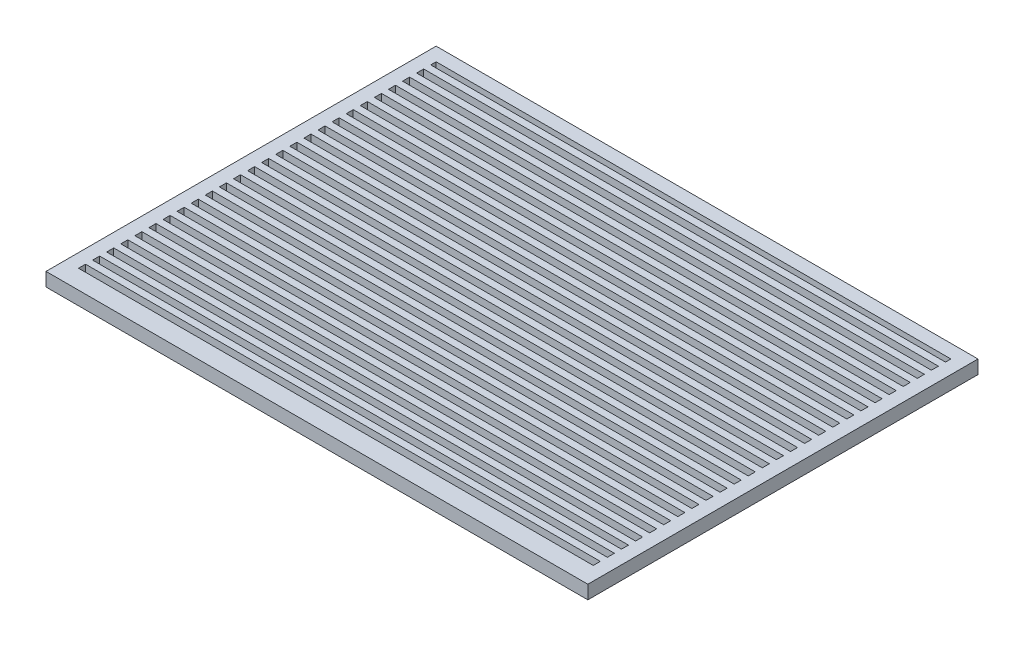
SolidWorks part; units mm, degrees
ref_plane "Front Plane" through (0, 0, 0) normal (0, 0, 1) x (1, 0, 0)
ref_plane "Top Plane" through (0, 0, 0) normal (0, 1, 0) x (1, 0, 0)
ref_plane "Right Plane" through (0, 0, 0) normal (1, 0, 0) x (0, 0, -1)
sketch "Sketch1" plane through (0, 0, 0) normal (0, 1, 0) x (1, 0, 0)
  line L1 (0, 0) -> (200, 0)
  line L2 (0, 0) -> (0, 144)
  line L3 (0, 144) -> (200, 144)
  line L4 (200, 0) -> (200, 144)
  dimension "D1" = 200
  dimension "D2" = 144
extrude "Boss-Extrude1" add sketch "Sketch1" along normal blind 5
sketch "Sketch2" plane through (0, 5, 0) normal (0, 1, 0) x (1, 0, 0)
  line L0 (0, 144) -> (0, 0) construction
  line L1 (5, 139) -> (195, 139)
  line L2 (5, 139) -> (5, 5)
  line L3 (5, 5) -> (195, 5)
  line L4 (195, 139) -> (195, 5)
  line L5 (200, 0) -> (200, 144) construction
  line L6 (200, 144) -> (0, 144) construction
  line L7 (0, 0) -> (200, 0) construction
  line L8 (5, 7) -> (195, 7)
  line L9 (195, 18.4551) -> (195, 31.4844)
  line L10 (5, 9.6) -> (195, 9.6)
  line L11 (5, 31.4844) -> (5, 45.5994)
  line L12 (5, 12.2) -> (195, 12.2)
  line L13 (195, 45.5994) -> (195, 72)
  line L14 (5, 14.8) -> (195, 14.8)
  line L15 (5, 72) -> (5, 70.9341)
  line L16 (5, 17.4) -> (195, 17.4)
  line L17 (5, 20) -> (195, 20)
  line L18 (5, 22.6) -> (195, 22.6)
  line L19 (5, 25.2) -> (195, 25.2)
  line L20 (5, 27.8) -> (195, 27.8)
  line L21 (5, 30.4) -> (195, 30.4)
  line L22 (5, 33) -> (195, 33)
  line L23 (5, 35.6) -> (195, 35.6)
  line L24 (5, 38.2) -> (195, 38.2)
  line L25 (5, 40.8) -> (195, 40.8)
  line L26 (5, 43.4) -> (195, 43.4)
  line L27 (5, 46) -> (195, 46)
  line L28 (5, 48.6) -> (195, 48.6)
  line L29 (5, 51.2) -> (195, 51.2)
  line L30 (5, 53.8) -> (195, 53.8)
  line L31 (5, 56.4) -> (195, 56.4)
  line L32 (5, 59) -> (195, 59)
  line L33 (5, 61.6) -> (195, 61.6)
  line L34 (5, 64.2) -> (195, 64.2)
  line L35 (5, 66.8) -> (195, 66.8)
  line L36 (5, 69.4) -> (195, 69.4)
  line L37 (5, 72) -> (195, 72)
  line L38 (5, 74.6) -> (195, 74.6)
  line L39 (5, 77.2) -> (195, 77.2)
  line L40 (5, 79.8) -> (195, 79.8)
  line L41 (5, 82.4) -> (195, 82.4)
  line L42 (5, 85) -> (195, 85)
  line L43 (5, 87.6) -> (195, 87.6)
  line L44 (5, 90.2) -> (195, 90.2)
  line L45 (5, 92.8) -> (195, 92.8)
  line L46 (5, 95.4) -> (195, 95.4)
  line L47 (5, 98) -> (195, 98)
  line L48 (5, 100.6) -> (195, 100.6)
  line L49 (5, 103.2) -> (195, 103.2)
  line L50 (5, 105.8) -> (195, 105.8)
  line L51 (5, 108.4) -> (195, 108.4)
  line L52 (5, 111) -> (195, 111)
  line L53 (5, 113.6) -> (195, 113.6)
  line L54 (5, 116.2) -> (195, 116.2)
  line L55 (5, 118.8) -> (195, 118.8)
  line L56 (5, 121.4) -> (195, 121.4)
  line L57 (5, 124) -> (195, 124)
  line L58 (5, 126.6) -> (195, 126.6)
  line L59 (5, 129.2) -> (195, 129.2)
  line L60 (5, 131.8) -> (195, 131.8)
  line L61 (5, 134.4) -> (195, 134.4)
  line L62 (5, 137) -> (195, 137)
  line L63 (5, 139.6) -> (195, 139.6)
  dimension "D1" = 5
  dimension "D2" = 5
  dimension "D3" = 5
  dimension "D4" = 5
  dimension "D5" = 2
  dimension "D6" = 52
extrude "Cut-Extrude1" cut sketch "Sketch2" against normal up to surface (5 mm away) contours L2 L62 L4 L1 | L61 L2 L60 L4 | L59 L2 L58 L4 | L57 L2 L56 L4 | L55 L2 L54 L4 | L53 L2 L52 L4 | L51 L2 L50 L4 | L49 L2 L48 L4 | L47 L2 L46 L4 | L45 L2 L44 L4 | L43 L2 L42 L4 | L41 L2 L40 L4 | L39 L2 L38 L4 | L37 L2 L36 L4 | L35 L2 L34 L13 | L33 L2 L32 L13 | L31 L2 L30 L13 | L29 L2 L28 L13 | L27 L2 L26 L4 L13 | L25 L11 L24 L4 | L23 L11 L22 L4 | L21 L2 L20 L9 | L19 L2 L18 L9 | L17 L2 L16 L4 L9 | L14 L2 L12 L4 | L10 L2 L8 L4 up to face at (100, 0, -72)
